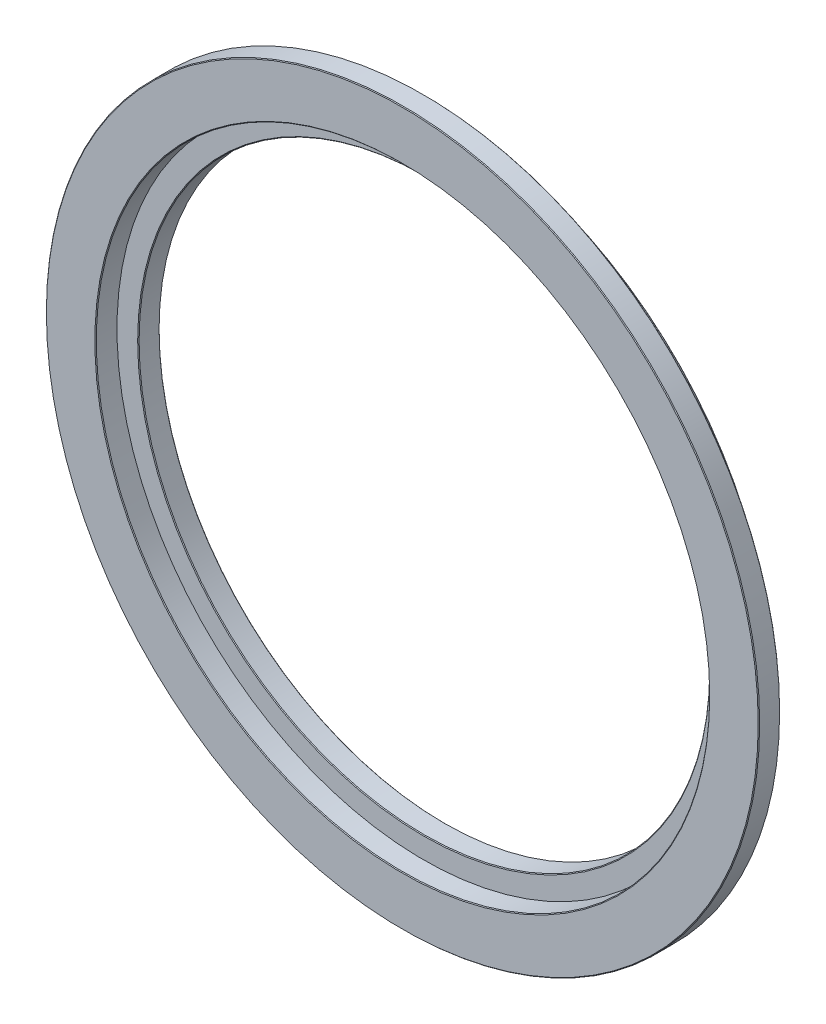
SolidWorks part; units mm, degrees
ref_plane "Front Plane" through (0, 0, 0) normal (0, 0, 1) x (1, 0, 0)
ref_plane "Top Plane" through (0, 0, 0) normal (0, 1, 0) x (1, 0, 0)
ref_plane "Right Plane" through (0, 0, 0) normal (1, 0, 0) x (0, 0, -1)
sketch "Sketch1" plane through (0, 0, 0) normal (1, 0, 0) x (0, 0, -1)
  line L0 (0, 40) -> (0, -44.8074) construction
  line L1 (-60.832, 0) -> (52.943, 0) construction
  line L2 (-0.1, 40) -> (-2.9, 40)
  line L3 (-3, 40.1) -> (-3, 43)
  line L4 (-3, 43) -> (-5.9, 43)
  line L5 (-6, 43.1) -> (-6, 49.9)
  line L6 (-5.9, 50) -> (-3.1, 50)
  line L7 (-3, 49.9) -> (-3, 46)
  line L8 (-3, 46) -> (-0.1, 46)
  line L9 (0, 45.9) -> (0, 40.1)
  line L10 (-6, 49.9) -> (-5.9, 50)
  line L11 (-3.1, 50) -> (-3, 49.9)
  line L12 (-0.1, 46) -> (0, 45.9)
  line L13 (0, 40.1) -> (-0.1, 40)
  line L14 (-2.9, 40) -> (-3, 40.1)
  line L15 (-5.9, 43) -> (-6, 43.1)
  point P5 (-6, 50)
  point P6 (-3, 40)
  point P8 (-6, 43)
  point P9 (-0.6222, 56.2003)
  point P10 (-3, 50)
  point P12 (0, 46)
  dimension "D1" = 40
  dimension "D2" = 3
  dimension "D3" = 3
  dimension "D4" = 7
  dimension "D5" = 3
  dimension "D6" = 4
  dimension "D7" = 6
revolve "Revolve1" add sketch "Sketch1" angle 360 about L1
